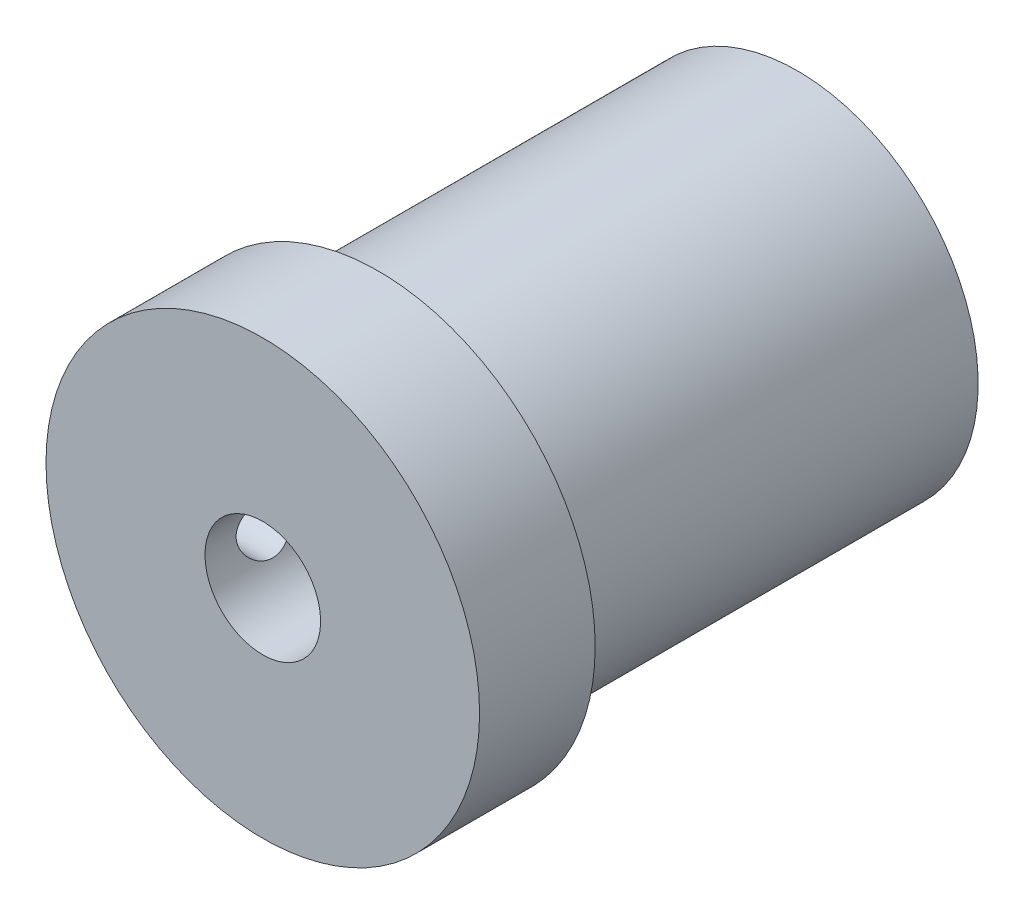
SolidWorks part; units mm, degrees
ref_plane "Front Plane" through (0, 0, 0) normal (0, 0, 1) x (1, 0, 0)
ref_plane "Top Plane" through (0, 0, 0) normal (0, 1, 0) x (1, 0, 0)
ref_plane "Right Plane" through (0, 0, 0) normal (1, 0, 0) x (0, 0, -1)
sketch "Sketch1" plane through (0, 0, 0) normal (0, 0, 1) x (1, 0, 0)
  circle A0 centre (0, 0) radius 12.5
  circle A1 centre (0, 0) radius 4
extrude "Boss-Extrude1" add sketch "Sketch1" along normal blind 29
sketch "Sketch2" plane through (0, 0, 29) normal (0, 0, 1) x (1, 0, 0)
  circle A0 centre (0, 0) radius 15
extrude "Boss-Extrude2" add sketch "Sketch2" along normal blind 8
sketch "Sketch3" plane through (0, 0, 0) normal (0, 0, -1) x (-1, 0, 0)
  circle A0 centre (0, 0) radius 4
extrude "Cut-Extrude2" cut sketch "Sketch3" against normal through all
hole_wizard "Ø4.0mm Dowel Hole1" positions "3DSketch4" profile "Sketch9" hole size "Ø4.0" standard "ISO"
sketch3d "3DSketch4"
  point P0 (-15, 0.0045, 32.8467)
sketch "Sketch9" plane through (-15, 0.0045, 32.8467) normal (0, 0, 1) x (-0.0003, -1, 0)
  line L0 (0, 0) -> (0, 11)
  line L1 (0, 11) -> (2, 11)
  line L2 (2, 11) -> (2, 0)
  line L5 (2, 0) -> (0, 0)
  line L11 (0, -6.35) -> (0, 107.95) construction
  dimension "Thru Hole Dia." = 4
  dimension "Thru Hole Depth" = 11
